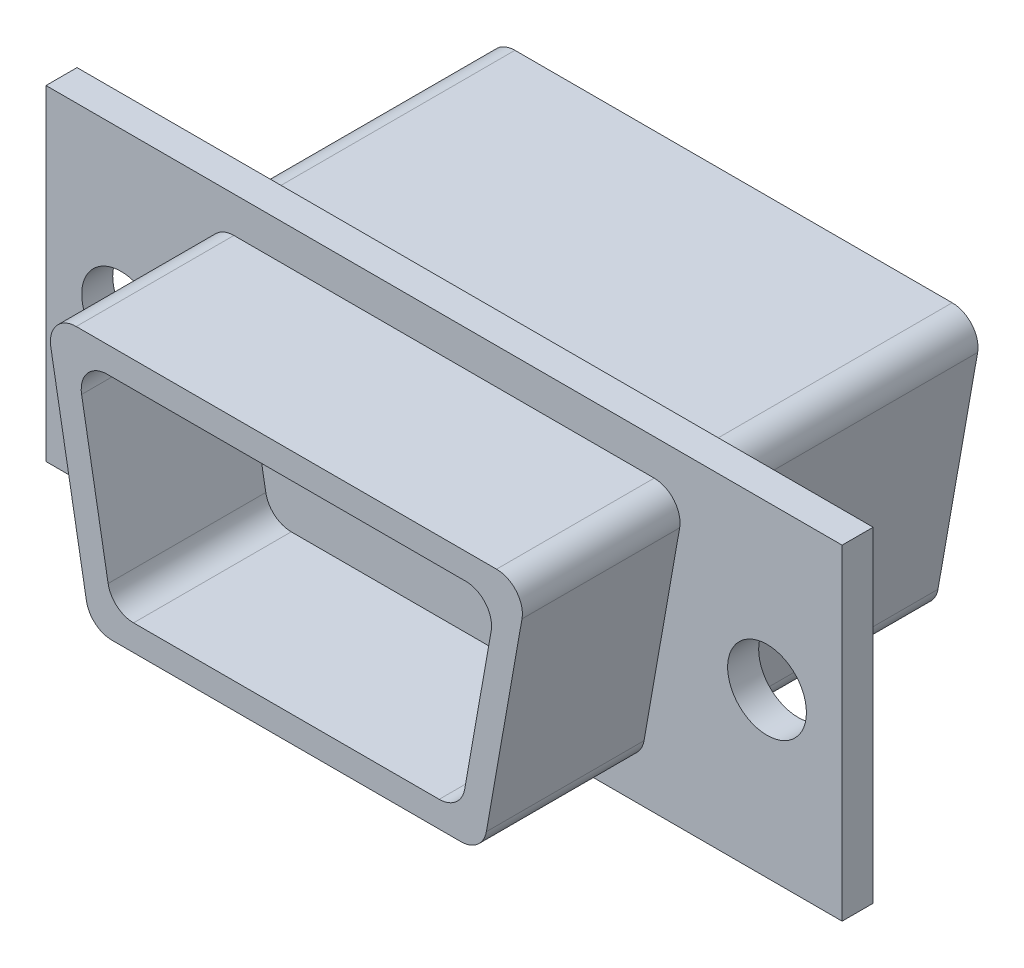
SolidWorks part; units mm, degrees
ref_plane "正面" through (0, 0, 0) normal (0, 0, 1) x (1, 0, 0)
ref_plane "平面" through (0, 0, 0) normal (0, 1, 0) x (1, 0, 0)
ref_plane "右側面" through (0, 0, 0) normal (1, 0, 0) x (0, 0, -1)
sketch "ｽｹｯﾁ1" plane through (0, 0, 0) normal (0, 0, 1) x (1, 0, 0)
  line L1 (-15.4, -6.3) -> (15.4, -6.3)
  line L2 (-15.4, -6.3) -> (-15.4, 6.3)
  line L3 (-15.4, 6.3) -> (15.4, 6.3)
  line L4 (15.4, -6.3) -> (15.4, 6.3)
  line L5 (-15.4, -6.3) -> (15.4, 6.3) construction
  line L6 (-15.4, 6.3) -> (15.4, -6.3) construction
  point P0 (0, 0)
  dimension "D1" = 30.8
  dimension "D2" = 12.6
extrude "ﾎﾞｽ - 押し出し1" add sketch "ｽｹｯﾁ1" along normal blind 1.2
sketch "ｽｹｯﾁ2" plane through (0, 0, 1.2) normal (0, 0, 1) x (1, 0, 0)
  line L0 (-8.13, 9.2752) -> (-8.13, -7.7701) construction
  line L1 (-6.7511, -3.91) -> (6.7511, -3.91)
  line L2 (-6.7511, -3.91) -> (-8.13, 3.91)
  line L3 (-8.13, 3.91) -> (8.13, 3.91)
  line L4 (6.7511, -3.91) -> (8.13, 3.91)
  line L5 (8.13, 9.2752) -> (8.13, -7.4612) construction
  line L6 (-9.3218, 4.91) -> (9.3218, 4.91)
  line L7 (7.5902, -4.91) -> (9.3218, 4.91)
  line L8 (-7.5902, -4.91) -> (7.5902, -4.91)
  line L9 (-7.5902, -4.91) -> (-9.3218, 4.91)
  point P0 (0, 0)
  dimension "D1" = 8.13
  dimension "D2" = 3.91
  dimension "D4" = 3.91
  dimension "D3" = 8.13
  dimension "D5" = 10
  dimension "D6" = 10
  dimension "D7" = 1
extrude "ﾎﾞｽ - 押し出し2" add sketch "ｽｹｯﾁ2" along normal blind 6.1
sketch "ｽｹｯﾁ3" plane through (0, 0, 0) normal (0, 0, -1) x (-1, 0, 0)
  line L0 (-9.65, 12.7623) -> (-9.65, -10.5928) construction
  line L1 (-7.7633, -5.35) -> (7.7633, -5.35)
  line L2 (-7.7633, -5.35) -> (-9.65, 5.35)
  line L3 (-9.65, 5.35) -> (9.65, 5.35)
  line L4 (7.7633, -5.35) -> (9.65, 5.35)
  line L7 (9.65, 13.0912) -> (9.65, -9.6882) construction
  point P0 (0, 0)
  dimension "D1" = 9.65
  dimension "D2" = 5.35
  dimension "D3" = 9.65
  dimension "D4" = 5.35
  dimension "D5" = 10
  dimension "D6" = 10
extrude "ﾎﾞｽ - 押し出し3" add sketch "ｽｹｯﾁ3" along normal blind 10
hole_wizard "#0000 すきま穴1" positions "3Dｽｹｯﾁ1" profile "ｽｹｯﾁ5" hole size "#0000" standard "Ansi Inch" end condition through all
sketch3d "3Dｽｹｯﾁ1"
  point P0 (-4.2254, 1.008, 1.2)
sketch "ｽｹｯﾁ5" plane through (-4.2254, 1.008, 1.2) normal (1, 0, 0) x (0, -1, 0)
  line L0 (0, 0) -> (0, 11.2)
  line L1 (0, 11.2) -> (0.3556, 11.2)
  line L2 (0.3556, 11.2) -> (0.3556, 0)
  line L5 (0.3556, 0) -> (0, 0)
  line L11 (0, -6.35) -> (0, 107.95) construction
  dimension "通し穴の直径" = 0.7112
  dimension "通し穴の深さ" = 11.2
hole_wizard "#0000 すきま穴2" positions "3Dｽｹｯﾁ2" profile "ｽｹｯﾁ6" hole size "#0000" standard "Ansi Inch" end condition through all
sketch3d "3Dｽｹｯﾁ2"
  point P0 (-3.1683, -1.2028, 1.2)
sketch "ｽｹｯﾁ6" plane through (-3.1683, -1.2028, 1.2) normal (1, 0, 0) x (0, -1, 0)
  line L0 (0, 0) -> (0, 11.2)
  line L1 (0, 11.2) -> (0.3556, 11.2)
  line L2 (0.3556, 11.2) -> (0.3556, 0)
  line L5 (0.3556, 0) -> (0, 0)
  line L11 (0, -6.35) -> (0, 107.95) construction
  dimension "通し穴の直径" = 0.7112
  dimension "通し穴の深さ" = 11.2
pattern_linear "直線ﾊﾟﾀｰﾝ1" count 5 spacing 2.54 along (1, 0, 0) of "#0000 すきま穴1"
pattern_linear "直線ﾊﾟﾀｰﾝ2" count 4 spacing 2.54 along (1, 0, 0) of "#0000 すきま穴2"
sketch "ｽｹｯﾁ8" plane through (0, 0, 1.2) normal (0, 0, 1) x (1, 0, 0)
  point P0 (-12.495, 0)
  point P1 (12.495, 0)
  dimension "D1" = 12.495
  dimension "D2" = 12.495
hole_wizard "#3 すきま穴2" positions "3Dｽｹｯﾁ4" profile "ｽｹｯﾁ9" hole size "#3" standard "Ansi Inch" end condition through all
sketch3d "3Dｽｹｯﾁ4"
  point P0 (-12.495, 0, 1.2)
  point P3 (12.495, 0, 1.2)
sketch "ｽｹｯﾁ9" plane through (-12.495, 0, 1.2) normal (1, 0, 0) x (0, -1, 0)
  line L0 (0, 0) -> (0, 11.2)
  line L1 (0, 11.2) -> (1.524, 11.2)
  line L2 (1.524, 11.2) -> (1.524, 0)
  line L5 (1.524, 0) -> (0, 0)
  line L11 (0, -6.35) -> (0, 107.95) construction
  dimension "通し穴の直径" = 3.048
  dimension "通し穴の深さ" = 11.2
fillet "ﾌｨﾚｯﾄ1" radius 1 12 edges at (-8.13, 3.91, 4.25) (-6.7511, -3.91, 4.25) (8.13, 3.91, 4.25) (6.7511, -3.91, 4.25) (7.7633, -5.35, -5) (9.65, 5.35, -5) (-7.7633, -5.35, -5) (-9.65, 5.35, -5) (9.3218, 4.91, 4.25) (7.5902, -4.91, 4.25) (-7.5902, -4.91, 4.25) (-9.3218, 4.91, 4.25)
